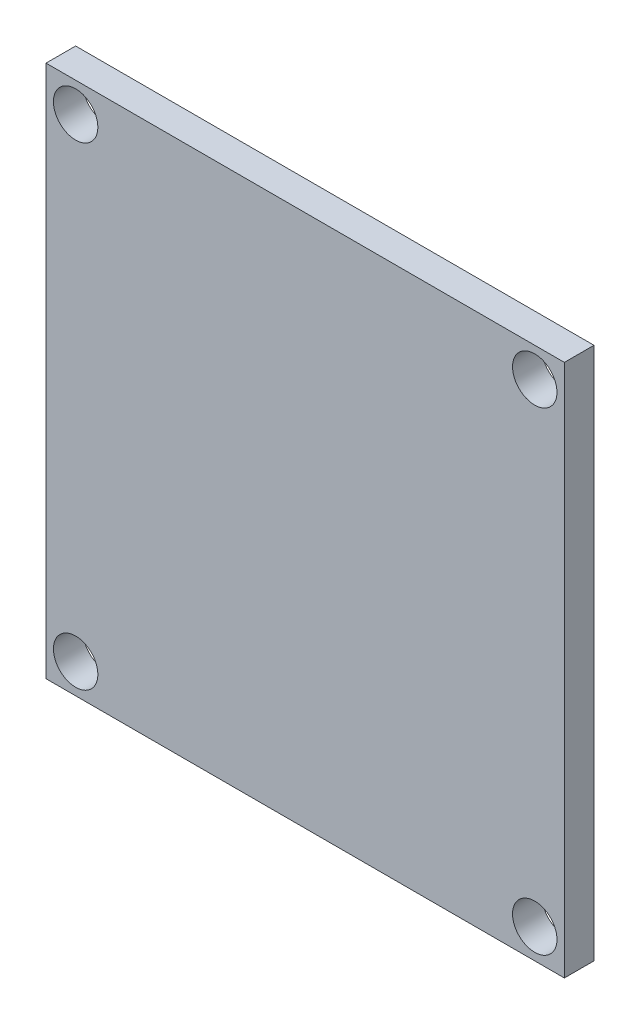
SolidWorks part; units mm, degrees
ref_plane "前视基准面" through (0, 0, 0) normal (0, 0, 1) x (1, 0, 0)
ref_plane "上视基准面" through (0, 0, 0) normal (0, 1, 0) x (1, 0, 0)
ref_plane "右视基准面" through (0, 0, 0) normal (1, 0, 0) x (0, 0, -1)
sketch "草图1" plane through (0, 0, 0) normal (0, 0, 1) x (1, 0, 0)
  line L1 (-17.5, 18) -> (17.5, 18)
  line L2 (-17.5, 18) -> (-17.5, -18)
  line L3 (-17.5, -18) -> (17.5, -18)
  line L4 (17.5, 18) -> (17.5, -18)
  line L5 (-17.5, 18) -> (17.5, -18) construction
  line L6 (-17.5, -18) -> (17.5, 18) construction
  point P0 (0, 0)
  dimension "D1" = 35
  dimension "D2" = 36
extrude "凸台-拉伸1" add sketch "草图1" along normal blind 2
sketch "草图2" plane through (0, 0, 2) normal (0, 0, 1) x (1, 0, 0)
  line L0 (17.5, 18) -> (-17.5, 18) construction
  line L1 (-17.5, 18) -> (-17.5, -18) construction
  line L2 (17.5, -18) -> (17.5, 18) construction
  line L3 (-17.5, -18) -> (17.5, -18) construction
  circle A0 centre (-15.5, 16) radius 1.5
  circle A1 centre (15.5, 16) radius 1.5
  circle A2 centre (15.5, -16) radius 1.5
  circle A3 centre (-15.5, -16) radius 1.5
  dimension "D3" = 3
  dimension "D4" = 3
  dimension "D7" = 3
  dimension "D10" = 3
  dimension "D1" = 2
  dimension "D2" = 2
  dimension "D5" = 2
  dimension "D6" = 2
  dimension "D8" = 2
  dimension "D9" = 2
  dimension "D11" = 2
  dimension "D12" = 2
extrude "切除-拉伸1" cut sketch "草图2" against normal up to next
